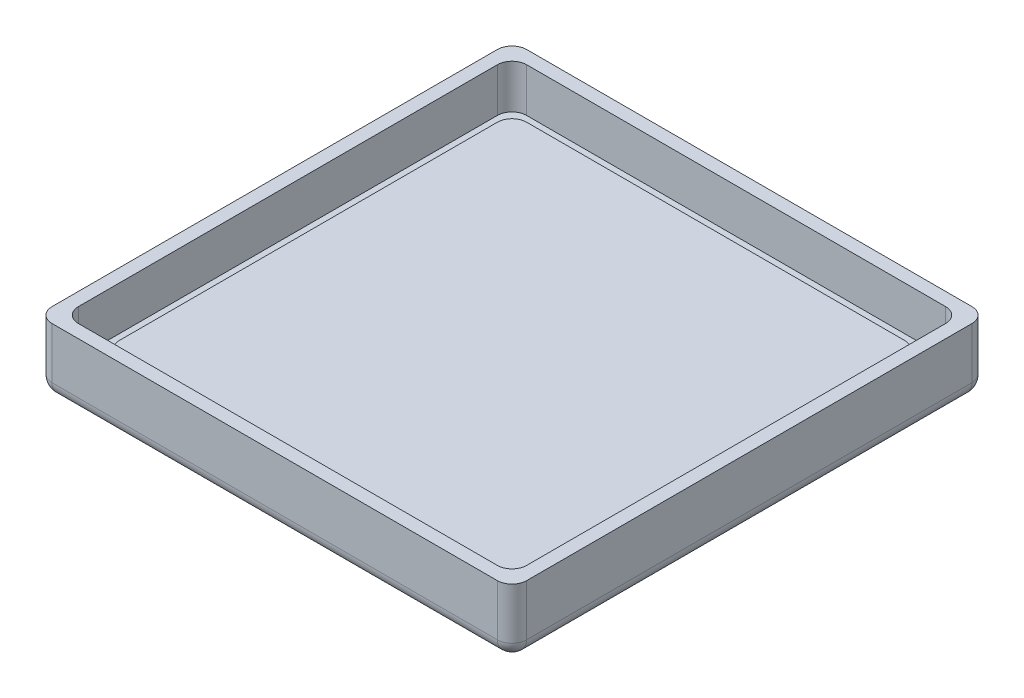
SolidWorks part; units mm, degrees
ref_plane "Front Plane" through (0, 0, 0) normal (0, 0, 1) x (1, 0, 0)
ref_plane "Top Plane" through (0, 0, 0) normal (0, 1, 0) x (1, 0, 0)
ref_plane "Right Plane" through (0, 0, 0) normal (1, 0, 0) x (0, 0, -1)
sketch "Sketch1" plane through (0, 0, 0) normal (0, 1, 0) x (1, 0, 0)
  line L1 (0, 0) -> (162, 0)
  line L2 (0, 0) -> (0, 162)
  line L3 (0, 162) -> (162, 162)
  line L4 (162, 0) -> (162, 162)
  line L5 (11, 151) -> (151, 151)
  line L6 (11, 151) -> (11, 11)
  line L7 (11, 11) -> (151, 11)
  line L8 (151, 151) -> (151, 11)
  dimension "D1" = 140
  dimension "D2" = 140
  dimension "D3" = 11
  dimension "D4" = 11
  dimension "D5" = 11
  dimension "D6" = 11
extrude "Boss-Extrude1" add sketch "Sketch1" along normal blind 7.5 contours L1 L4 L3 L2 L5 L8 L7 L6 | L8 L5 L6 L7
sketch "Sketch2" plane through (0, 7.5, 0) normal (0, 1, 0) x (1, 0, 0)
  line L0 (162, 0) -> (162, 162) construction
  line L1 (11.5, 150.5) -> (150.5, 150.5)
  line L2 (11.5, 150.5) -> (11.5, 11.5)
  line L3 (11.5, 11.5) -> (150.5, 11.5)
  line L4 (150.5, 150.5) -> (150.5, 11.5)
  line L5 (0, 0) -> (0, 162) construction
  line L6 (0, 0) -> (162, 0) construction
  line L7 (0, 162) -> (162, 162) construction
  dimension "D1" = 11.5
  dimension "D2" = 11.5
  dimension "D3" = 11.5
  dimension "D4" = 11.5
extrude "Boss-Extrude2" add sketch "Sketch2" along normal blind 5
fillet "Fillet1" radius 5 12 edges at (150.5, 10, -150.5) (150.5, 10, -11.5) (0, 3.75, 0) (81, 0, 0) (162, 3.75, 0) (162, 0, -81) (81, 0, -162) (162, 3.75, -162) (0, 3.75, -162) (11.5, 10, -150.5) (11.5, 10, -11.5) (0, 0, -81)
sketch "Sketch3" plane through (0, 7.5, 0) normal (0, 1, 0) x (1, 0, 0)
  line L0 (0, 5) -> (0, 157) construction
  line L1 (9.5, 157.5) -> (152.5, 157.5)
  line L2 (4.5, 152.5) -> (4.5, 9.5)
  line L3 (9.5, 4.5) -> (152.5, 4.5)
  line L4 (157.5, 152.5) -> (157.5, 9.5)
  line L5 (162, 5) -> (162, 157) construction
  line L6 (5, 162) -> (157, 162) construction
  line L7 (5, 0) -> (157, 0) construction
  arc A0 (4.5, 9.5) -> (9.5, 4.5) centre (9.5, 9.5) ccw
  arc A1 (152.5, 4.5) -> (157.5, 9.5) centre (152.5, 9.5) ccw
  arc A2 (152.5, 157.5) -> (157.5, 152.5) centre (152.5, 152.5) cw
  arc A3 (9.5, 157.5) -> (4.5, 152.5) centre (9.5, 152.5) ccw
  line M13 (0, 157) -> (0, 5)
  arc M14 (0, 5) -> (5, 0) centre (5, 5) ccw
  line M15 (5, 0) -> (157, 0)
  arc M16 (157, 0) -> (162, 5) centre (157, 5) ccw
  line M17 (162, 5) -> (162, 157)
  arc M18 (162, 157) -> (157, 162) centre (157, 157) ccw
  line M19 (157, 162) -> (5, 162)
  arc M20 (5, 162) -> (0, 157) centre (5, 157) ccw
  dimension "D5" = 5
  dimension "D1" = 4.5
  dimension "D2" = 4.5
  dimension "D3" = 4.5
  dimension "D4" = 4.5
extrude "Boss-Extrude3" add sketch "Sketch3" along normal blind 15 contours A3 L1 A2 L4 A1 L3 A0 L2 M20 M13 M14 M15 M16 M17 M18 M19
